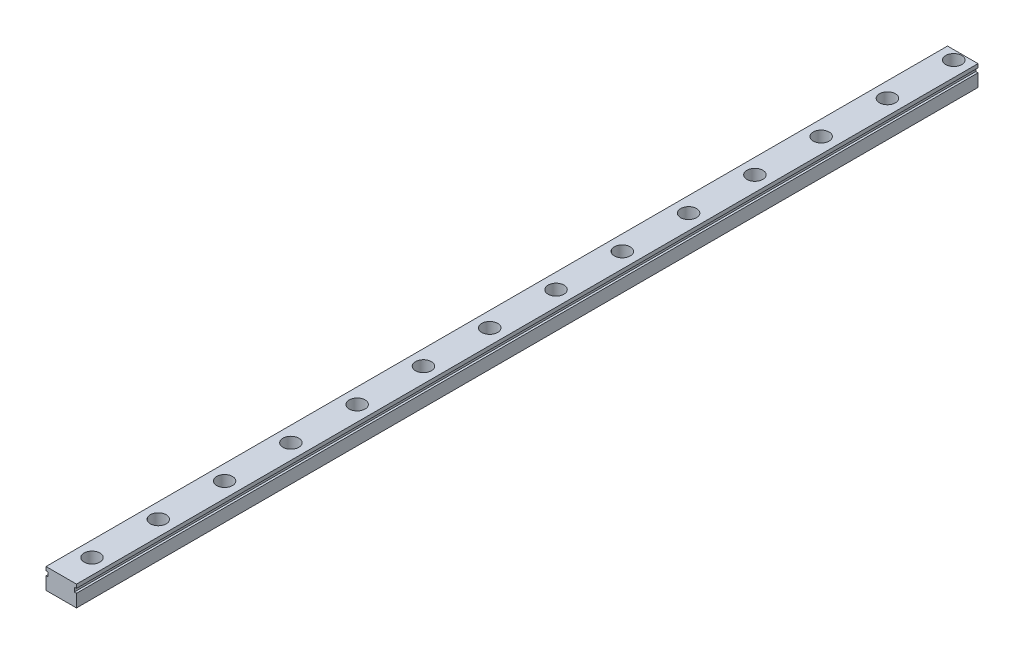
SolidWorks part; units mm, degrees
ref_plane "Front Plane" through (0, 0, 0) normal (0, 0, 1) x (1, 0, 0)
ref_plane "Top Plane" through (0, 0, 0) normal (0, 1, 0) x (1, 0, 0)
ref_plane "Right Plane" through (0, 0, 0) normal (1, 0, 0) x (0, 0, -1)
sketch "Sketch1" plane through (0, 0, 0) normal (0, 0, 1) x (1, 0, 0)
  line L1 (-5.75, -3.9) -> (5.75, -3.9)
  line L2 (-5.75, -3.9) -> (-5.75, 3.9)
  line L3 (-5.75, 3.9) -> (5.75, 3.9)
  line L4 (5.75, -3.9) -> (5.75, 3.9)
  line L5 (-5.75, -3.9) -> (5.75, 3.9) construction
  line L6 (-5.75, 3.9) -> (5.75, -3.9) construction
  point P0 (0, 0)
  dimension "D1" = 11.5
  dimension "D2" = 7.8
extrude "Boss-Extrude1" add sketch "Sketch1" along normal blind 340
sketch "Sketch2" plane through (0, 0, 340) normal (0, 0, 1) x (1, 0, 0)
  line L0 (5.75, -3.9) -> (5.75, 3.9) construction
  line L1 (5.75, 2.5) -> (4.9147, 2.5)
  line L2 (5.75, 2.5) -> (5.75, 0.9)
  line L3 (5.75, 0.9) -> (4.9147, 0.9)
  line L4 (4.9147, 2.5) -> (4.9147, 0.9)
  line L5 (5.75, 3.9) -> (-5.75, 3.9) construction
  line L7 (0, -4.29) -> (0, 4.29) construction
  line L8 (-5.75, 0.9) -> (-4.9147, 0.9)
  line L9 (-4.9147, 2.5) -> (-4.9147, 0.9)
  line L10 (-5.75, 2.5) -> (-4.9147, 2.5)
  line L11 (-5.75, 2.5) -> (-5.75, 0.9)
  dimension "D1" = 1.4
  dimension "D2" = 1.6
extrude "Cut-Extrude1" cut sketch "Sketch2" against normal through all
sketch "Sketch3" plane through (0, 3.9, 0) normal (0, 1, 0) x (1, 0, 0)
  line L0 (0, -223.2) -> (0, -215.9183) construction
  line L2 (5.75, -340) -> (-5.75, -340) construction
  circle A0 centre (0, -328.4) radius 3
  circle A1 centre (0, -303.4) radius 3
  circle A2 centre (0, -278.4) radius 3
  circle A3 centre (0, -253.4) radius 3
  circle A4 centre (0, -228.4) radius 3
  circle A5 centre (0, -203.4) radius 3
  circle A6 centre (0, -178.4) radius 3
  circle A7 centre (0, -153.4) radius 3
  circle A8 centre (0, -128.4) radius 3
  circle A9 centre (0, -103.4) radius 3
  circle A10 centre (0, -78.4) radius 3
  circle A11 centre (0, -53.4) radius 3
  circle A12 centre (0, -28.4) radius 3
  circle A13 centre (0, -3.4) radius 3
  circle A14 centre (0, 21.6) radius 3
  circle A15 centre (0, 46.6) radius 3
  circle A16 centre (0, 71.6) radius 3
  circle A17 centre (0, 96.6) radius 3
  circle A18 centre (0, 121.6) radius 3
  circle A19 centre (0, 146.6) radius 3
  circle A20 centre (0, 171.6) radius 3
  circle A21 centre (0, 196.6) radius 3
  circle A22 centre (0, 221.6) radius 3
  circle A23 centre (0, 246.6) radius 3
  circle A24 centre (0, 271.6) radius 3
  dimension "D1" = 11.6
  dimension "D2" = 6
  dimension "D3" = 25
extrude "Cut-Extrude2" cut sketch "Sketch3" against normal blind 4.7
sketch "Sketch4" plane through (0, -0.8, 0) normal (0, 1, 0) x (1, 0, 0)
  circle A0 centre (0, -328.4) radius 1.7
  circle A1 centre (0, -303.4) radius 1.7
  circle A2 centre (0, -278.4) radius 1.7
  circle A3 centre (0, -253.4) radius 1.7
  circle A4 centre (0, -228.4) radius 1.7
  circle A5 centre (0, -203.4) radius 1.7
  circle A6 centre (0, -178.4) radius 1.7
  circle A7 centre (0, -153.4) radius 1.7
  circle A8 centre (0, -128.4) radius 1.7
  circle A9 centre (0, -103.4) radius 1.7
  circle A10 centre (0, -78.4) radius 1.7
  circle A11 centre (0, -53.4) radius 1.7
  circle A12 centre (0, -28.4) radius 1.7
  circle A13 centre (0, -3.4) radius 1.7
  circle A14 centre (0, 21.6) radius 1.7
  circle A15 centre (0, 46.6) radius 1.7
  circle A16 centre (0, 71.6) radius 1.7
  circle A17 centre (0, 96.6) radius 1.7
  circle A18 centre (0, 121.6) radius 1.7
  circle A19 centre (0, 146.6) radius 1.7
  circle A20 centre (0, 171.6) radius 1.7
  circle A21 centre (0, 196.6) radius 1.7
  circle A22 centre (0, 221.6) radius 1.7
  circle A23 centre (0, 246.6) radius 1.7
  circle A24 centre (0, 271.6) radius 1.7
  dimension "D1" = 3.4
  dimension "D2" = 25
extrude "Cut-Extrude3" cut sketch "Sketch4" against normal through all
